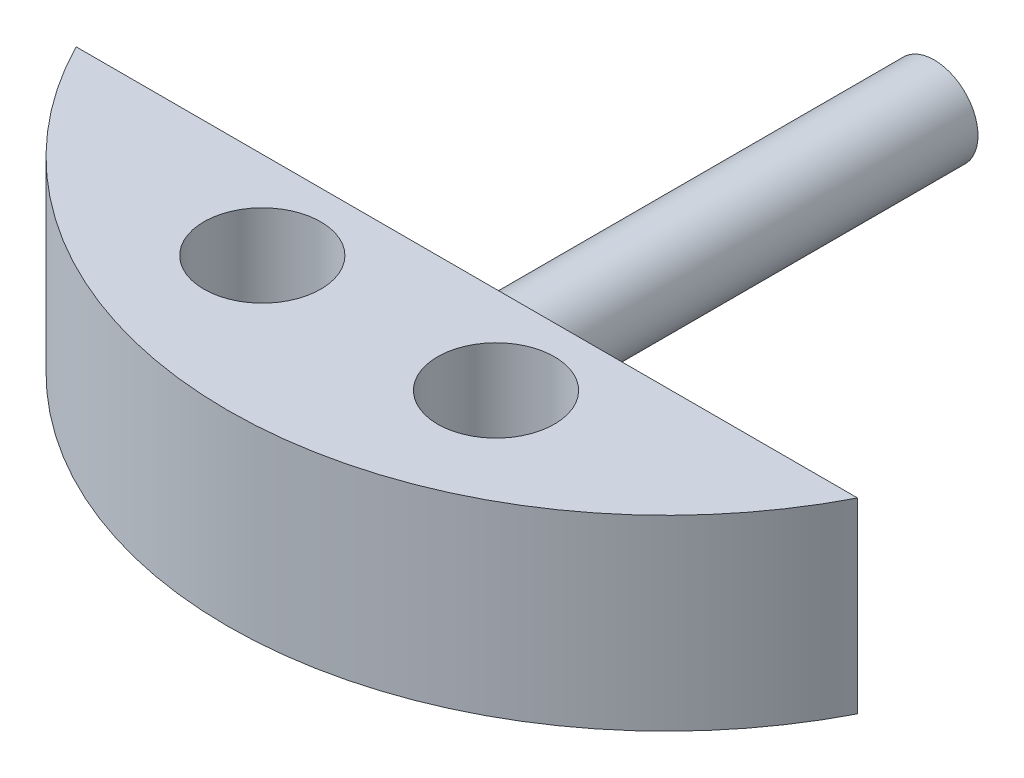
SolidWorks part; units mm, degrees
material "Alumina"
ref_plane "Front Plane" through (0, 0, 0) normal (0, 0, 1) x (1, 0, 0)
ref_plane "Top Plane" through (0, 0, 0) normal (0, 1, 0) x (1, 0, 0)
ref_plane "Right Plane" through (0, 0, 0) normal (1, 0, 0) x (0, 0, -1)
sketch "Sketch1" plane through (0, 0, 0) normal (0, 1, 0) x (1, 0, 0)
  line L0 (-12.7, -26.4729) -> (12.7, -26.4729) construction
  line L1 (-42.46, -21.7104) -> (42.46, -21.7104)
  circle A0 centre (0, 0) radius 47.6885 construction
  circle A1 centre (-12.7, -31.2354) radius 4.7625 construction
  circle A2 centre (12.7, -31.2354) radius 4.7625 construction
  circle A3 centre (12.7, -31.2354) radius 12.7 construction
  circle A4 centre (12.7, -31.2354) radius 13.97 construction
  circle A5 centre (-12.7, -31.2354) radius 12.7 construction
  circle A6 centre (-12.7, -31.2354) radius 13.97 construction
  circle A7 centre (-12.7, -31.2354) radius 6.35
  circle A8 centre (12.7, -31.2354) radius 6.35
  arc A9 (-42.46, -21.7104) -> (42.46, -21.7104) centre (0, 0) ccw
  dimension "D1" = 95.377
  dimension "D2" = 27.94
  dimension "D3" = 25.4
  dimension "D4" = 9.525
  dimension "D7" = 4.7625
  dimension "D5" = 12.7
  dimension "D6" = 12.7
extrude "Boss-Extrude1" add sketch "Sketch1" along normal blind 20.32
sketch "Sketch2" plane through (0, 0, 21.7104) normal (0, 0, -1) x (-1, 0, 0)
  line L0 (0, 0) -> (0, 20.32) construction
  line L1 (-42.46, 20.32) -> (42.46, 20.32) construction
  line L2 (-42.46, 0) -> (42.46, 0) construction
  circle A0 centre (0, 10.16) radius 4.7498
  point P11 (0, 0)
  point P14 (0, 0)
  point P15 (0, 0)
  point P16 (0, 0)
  dimension "D2" = 9.4996
  dimension "D3" = 10.16
extrude "Boss-Extrude2" add sketch "Sketch2" along normal blind 50.8
sketch "Sketch3" plane through (0, 20.32, 0) normal (0, 1, 0) x (1, 0, 0)
  arc A0 (-42.46, -21.7104) -> (42.46, -21.7104) centre (0, 0) ccw construction
  point P0 (0, -47.6885)
